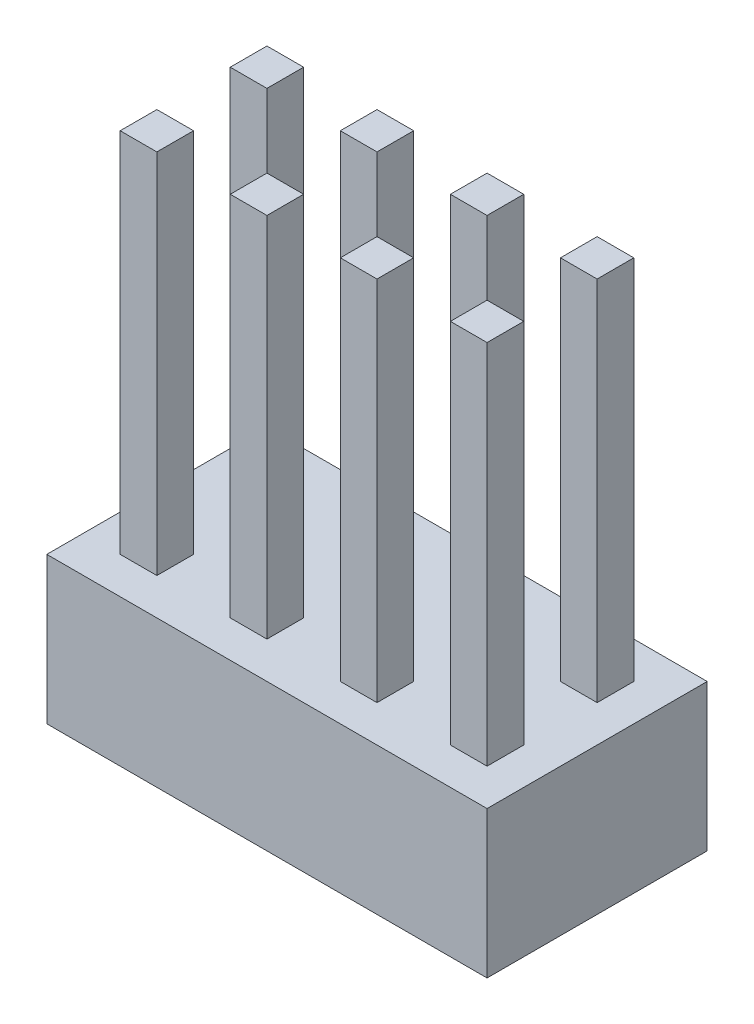
SolidWorks part; units mm, degrees
ref_plane "Front Plane" through (0, 0, 0) normal (0, 0, 1) x (1, 0, 0)
ref_plane "Top Plane" through (0, 0, 0) normal (0, 1, 0) x (1, 0, 0)
ref_plane "Right Plane" through (0, 0, 0) normal (1, 0, 0) x (0, 0, -1)
sketch "Sketch1" plane through (0, 0, 0) normal (0, 1, 0) x (1, 0, 0)
  line L1 (0, 0) -> (9.144, 0)
  line L2 (0, 0) -> (0, 4.572)
  line L3 (0, 4.572) -> (9.144, 4.572)
  line L4 (9.144, 0) -> (9.144, 4.572)
  dimension "D1" = 9.144
  dimension "D2" = 4.572
extrude "Extrude1" add sketch "Sketch1" along normal blind 3.048
sketch "Sketch2" plane through (0, 3.048, 0) normal (0, 1, 0) x (1, 0, 0)
  line L0 (0, 4.572) -> (0, 0) construction
  line L1 (3.048, 3.048) -> (3.048, 3.81)
  line L2 (3.048, 3.81) -> (3.81, 3.81)
  line L3 (3.81, 3.048) -> (3.81, 3.81)
  line L4 (3.048, 3.048) -> (3.81, 3.048)
  line L5 (0.762, 3.048) -> (1.524, 3.048)
  line L6 (0.762, 3.048) -> (0.762, 3.81)
  line L7 (0.762, 3.81) -> (1.524, 3.81)
  line L8 (1.524, 3.048) -> (1.524, 3.81)
  line L9 (5.334, 3.048) -> (5.334, 3.81)
  line L10 (9.144, 4.572) -> (0, 4.572) construction
  line L11 (5.334, 3.81) -> (6.096, 3.81)
  line L12 (6.096, 3.048) -> (6.096, 3.81)
  line L13 (5.334, 3.048) -> (6.096, 3.048)
  line L14 (7.62, 3.048) -> (7.62, 3.81)
  line L15 (7.62, 3.81) -> (8.382, 3.81)
  line L16 (8.382, 3.048) -> (8.382, 3.81)
  line L17 (7.62, 3.048) -> (8.382, 3.048)
  line L18 (0.762, 0.762) -> (0.762, 1.524)
  line L19 (0.762, 1.524) -> (1.524, 1.524)
  line L20 (1.524, 0.762) -> (1.524, 1.524)
  line L21 (0.762, 0.762) -> (1.524, 0.762)
  line L22 (3.048, 0.762) -> (3.048, 1.524)
  line L23 (3.048, 1.524) -> (3.81, 1.524)
  line L24 (3.81, 0.762) -> (3.81, 1.524)
  line L25 (3.048, 0.762) -> (3.81, 0.762)
  line L26 (5.334, 0.762) -> (5.334, 1.524)
  line L27 (5.334, 1.524) -> (6.096, 1.524)
  line L28 (6.096, 0.762) -> (6.096, 1.524)
  line L29 (5.334, 0.762) -> (6.096, 0.762)
  line L30 (7.62, 0.762) -> (7.62, 1.524)
  line L31 (7.62, 1.524) -> (8.382, 1.524)
  line L32 (8.382, 0.762) -> (8.382, 1.524)
  line L33 (7.62, 0.762) -> (8.382, 0.762)
  dimension "D3" = 0.762
  dimension "D4" = 0.762
  dimension "D5" = 0.762
  dimension "D8" = 0.762
extrude "Extrude2" add sketch "Sketch2" along normal blind 7.62
